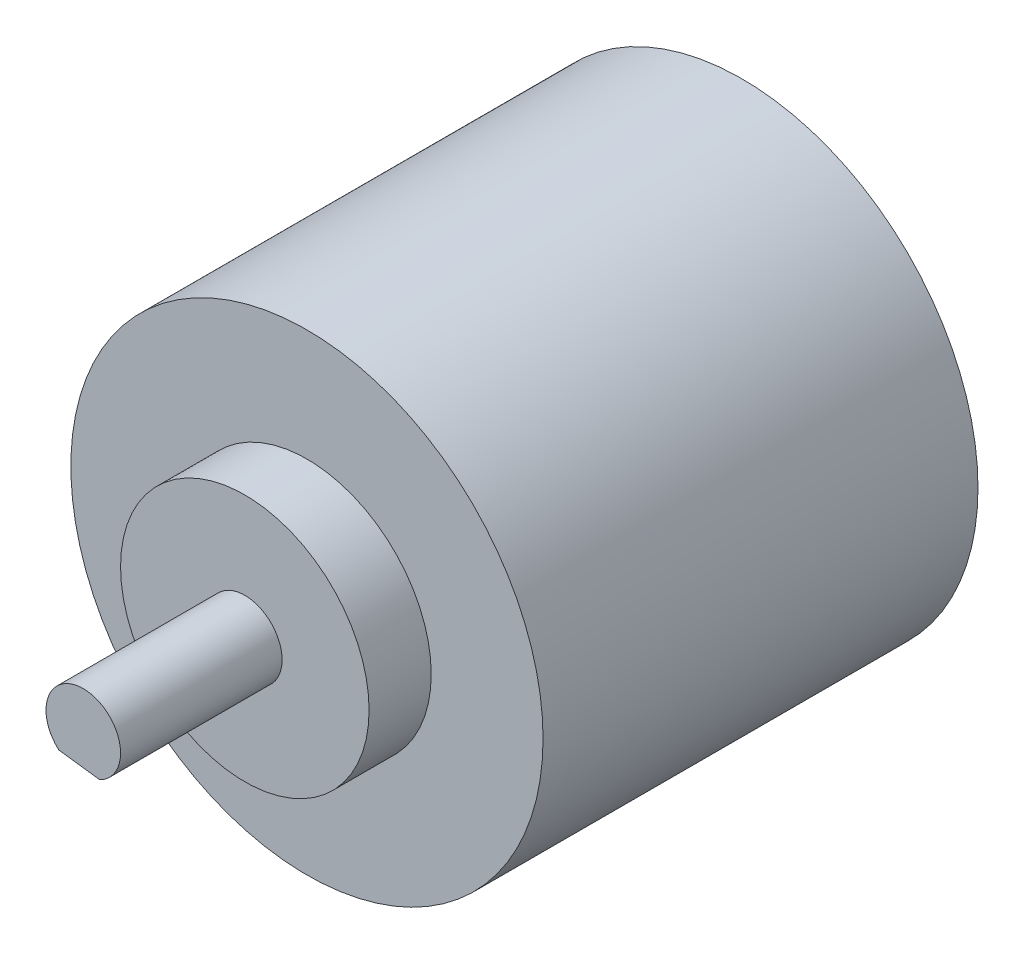
SolidWorks part; units mm, degrees
material "Rubber"
ref_plane "Front Plane" through (0, 0, 0) normal (0, 0, 1) x (1, 0, 0)
ref_plane "Top Plane" through (0, 0, 0) normal (0, 1, 0) x (1, 0, 0)
ref_plane "Right Plane" through (0, 0, 0) normal (1, 0, 0) x (0, 0, -1)
sketch "Sketch1" plane through (0, 0, 0) normal (0, 0, 1) x (1, 0, 0)
  circle A0 centre (0, 0) radius 19
  dimension "D1" = 38
extrude "Boss-Extrude1" add sketch "Sketch1" along normal blind 35
sketch "Sketch2" plane through (0, 0, 35) normal (0, 0, 1) x (1, 0, 0)
  circle A0 centre (0, 0) radius 10
  dimension "D1" = 20
extrude "Boss-Extrude2" add sketch "Sketch2" along normal blind 5
sketch "Sketch3" plane through (0, 0, 40) normal (0, 0, 1) x (1, 0, 0)
  circle A0 centre (0, 0) radius 3
  dimension "D1" = 6
extrude "Boss-Extrude3" add sketch "Sketch3" along normal blind 13
sketch "Sketch4" plane through (0, 0, 53) normal (0, 0, 1) x (1, 0, 0)
  line L0 (-1.9671, -2.2651) -> (1.3218, -2.6931)
  arc A0 (-1.9671, -2.2651) -> (1.3218, -2.6931) centre (0, 0) ccw
  dimension "D2" = 6
  dimension "D1" = 2.5
extrude "Cut-Extrude1" cut sketch "Sketch4" against normal blind 13
